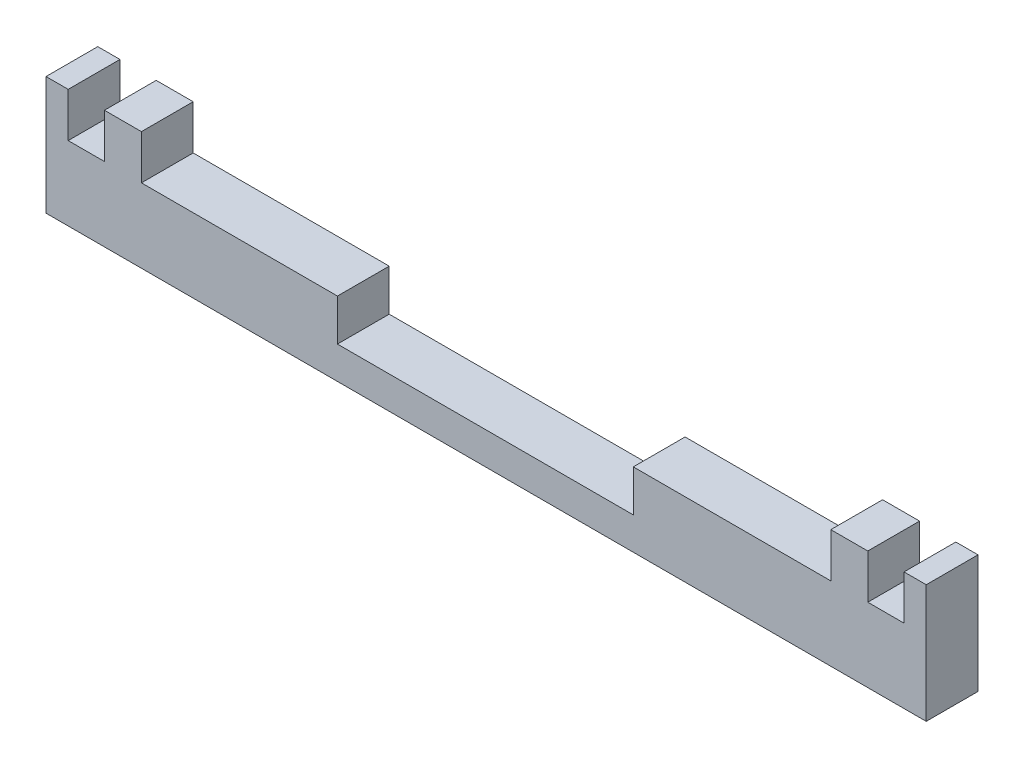
SolidWorks part; units mm, degrees
ref_plane "Front Plane" through (0, 0, 0) normal (0, 0, 1) x (1, 0, 0)
ref_plane "Top Plane" through (0, 0, 0) normal (0, 1, 0) x (1, 0, 0)
ref_plane "Right Plane" through (0, 0, 0) normal (1, 0, 0) x (0, 0, -1)
sketch "Sketch1" plane through (0, 0, 0) normal (0, 0, 1) x (1, 0, 0)
  line L8 (-95.4472, -23.6971) -> (55.6828, -23.6971)
  line L9 (55.6828, -23.6971) -> (55.6828, -3.3771)
  line L10 (55.6828, -3.3771) -> (51.8728, -3.3771)
  line L11 (51.8728, -3.3771) -> (51.8728, -10.9971)
  line L12 (51.8728, -10.9971) -> (45.6498, -10.9971)
  line L13 (45.6498, -10.9971) -> (45.6498, -3.3771)
  line L14 (45.6498, -3.3771) -> (39.2998, -3.3771)
  line L15 (39.2998, -3.3771) -> (39.2998, -10.9971)
  line L16 (39.2998, -10.9971) -> (-79.0642, -10.9971)
  line L17 (-79.0642, -10.9971) -> (-79.0642, -3.3771)
  line L18 (-79.0642, -3.3771) -> (-85.4142, -3.3771)
  line L19 (-85.4142, -3.3771) -> (-85.4142, -10.9971)
  line L20 (-85.4142, -10.9971) -> (-91.6372, -10.9971)
  line L21 (-91.6372, -10.9971) -> (-91.6372, -3.3771)
  line L22 (-91.6372, -3.3771) -> (-95.4472, -3.3771)
  line L23 (-95.4472, -3.3771) -> (-95.4472, -23.6971)
  point P2 (-88.5257, -10.9971)
  point P17 (48.7613, -10.9971)
  dimension "D1" = 137.287
  dimension "D2" = 6.223
  dimension "D3" = 6.223
  dimension "D4" = 7.62
  dimension "D5" = 6.35
  dimension "D6" = 7.62
  dimension "D7" = 7.62
  dimension "D8" = 7.62
  dimension "D9" = 3.81
  dimension "D10" = 3.81
  dimension "D11" = 6.35
  dimension "D12" = 12.7
extrude "Boss-Extrude1" add sketch "Sketch1" along normal blind 8.89
sketch "Sketch2" plane through (0, 0, 8.89) normal (0, 0, 1) x (1, 0, 0)
  line L0 (39.2998, -10.9971) -> (-79.0642, -10.9971) construction
  line L1 (-45.4092, -10.9971) -> (5.3908, -10.9971)
  line L2 (-45.4092, -10.9971) -> (-45.4092, -18.1409)
  line L3 (-45.4092, -18.1409) -> (5.3908, -18.1409)
  line L4 (5.3908, -10.9971) -> (5.3908, -18.1409)
  line L5 (-95.4472, -3.3771) -> (-95.4472, -23.6971) construction
  point P6 (-20.0092, -10.9971)
  dimension "D1" = 7.1437
  dimension "D2" = 75.438
  dimension "D3" = 50.8
extrude "Cut-Extrude1" cut sketch "Sketch2" against normal blind 8.89
